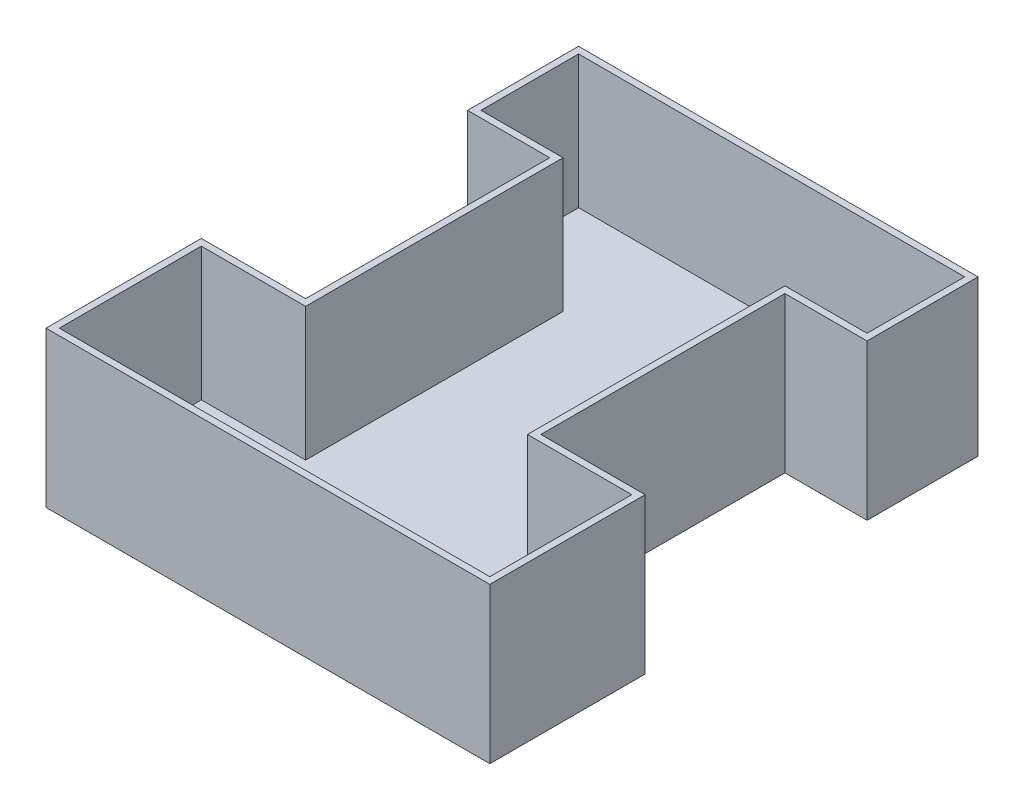
SolidWorks part; units mm, degrees
ref_plane "Front Plane" through (0, 0, 0) normal (0, 0, 1) x (1, 0, 0)
ref_plane "Top Plane" through (0, 0, 0) normal (0, 1, 0) x (1, 0, 0)
ref_plane "Right Plane" through (0, 0, 0) normal (1, 0, 0) x (0, 0, -1)
sketch "Sketch1" plane through (0, 0, 0) normal (0, 1, 0) x (1, 0, 0)
  line L0 (0, 77.0548) -> (0, -93.9041) construction
  line L1 (72.2603, 79.863) -> (-107.7397, 79.863)
  line L2 (-107.7397, 79.863) -> (-107.7397, 29.863)
  line L3 (-107.7397, 29.863) -> (-70.7397, 29.863)
  line L4 (-70.7397, 29.863) -> (-70.7397, -80.137)
  line L5 (-70.7397, -80.137) -> (-117.7397, -80.137)
  line L6 (-117.7397, -80.137) -> (-117.7397, -150.137)
  line L7 (-117.7397, -150.137) -> (82.2603, -150.137)
  line L8 (82.2603, -150.137) -> (82.2603, -80.137)
  line L9 (82.2603, -80.137) -> (35.2603, -80.137)
  line L10 (35.2603, -80.137) -> (35.2603, 29.863)
  line L11 (35.2603, 29.863) -> (72.2603, 29.863)
  line L12 (72.2603, 29.863) -> (72.2603, 79.863)
  line L13 (69.2603, 76.863) -> (-104.7397, 76.863)
  line L14 (-104.7397, 76.863) -> (-104.7397, 32.863)
  line L15 (-104.7397, 32.863) -> (-67.7397, 32.863)
  line L16 (-67.7397, 32.863) -> (-67.7397, -83.137)
  line L17 (-67.7397, -83.137) -> (-114.7397, -83.137)
  line L18 (-114.7397, -83.137) -> (-114.7397, -147.137)
  line L19 (-114.7397, -147.137) -> (79.2603, -147.137)
  line L20 (79.2603, -147.137) -> (79.2603, -83.137)
  line L21 (79.2603, -83.137) -> (32.2603, -83.137)
  line L22 (32.2603, -83.137) -> (32.2603, 32.863)
  line L23 (32.2603, 32.863) -> (69.2603, 32.863)
  line L24 (69.2603, 32.863) -> (69.2603, 76.863)
  dimension "D1" = 180
  dimension "D2" = 50
  dimension "D3" = 50
  dimension "D4" = 200
  dimension "D5" = 47
  dimension "D6" = 37
  dimension "D7" = 37
  dimension "D8" = 47
  dimension "D9" = 70
  dimension "D10" = 70
  dimension "D11" = 110
  dimension "D12" = 110
  dimension "D13" = 37
  dimension "D14" = 3
extrude "Boss-Extrude1" add sketch "Sketch1" along normal blind 60
sketch "Sketch2" plane through (0, 0, 0) normal (0, 1, 0) x (1, 0, 0)
  line L12 (72.2603, 29.863) -> (72.2603, 79.863)
  line L13 (72.2603, 79.863) -> (-107.7397, 79.863)
  line L14 (-107.7397, 79.863) -> (-107.7397, 29.863)
  line L15 (-107.7397, 29.863) -> (-70.7397, 29.863)
  line L16 (-70.7397, 29.863) -> (-70.7397, -80.137)
  line L17 (-70.7397, -80.137) -> (-117.7397, -80.137)
  line L18 (-117.7397, -80.137) -> (-117.7397, -150.137)
  line L19 (-117.7397, -150.137) -> (82.2603, -150.137)
  line L20 (82.2603, -150.137) -> (82.2603, -80.137)
  line L21 (82.2603, -80.137) -> (35.2603, -80.137)
  line L22 (35.2603, -80.137) -> (35.2603, 29.863)
  line L23 (35.2603, 29.863) -> (72.2603, 29.863)
  line L24 (72.2603, 29.863) -> (72.2603, 79.863)
  line L25 (72.2603, 79.863) -> (-107.7397, 79.863)
  line L26 (-107.7397, 79.863) -> (-107.7397, 29.863)
  line L27 (-107.7397, 29.863) -> (-70.7397, 29.863)
  line L28 (-70.7397, 29.863) -> (-70.7397, -80.137)
  line L29 (-70.7397, -80.137) -> (-117.7397, -80.137)
  line L30 (-117.7397, -80.137) -> (-117.7397, -150.137)
  line L31 (-117.7397, -150.137) -> (82.2603, -150.137)
  line L32 (82.2603, -150.137) -> (82.2603, -80.137)
  line L33 (82.2603, -80.137) -> (35.2603, -80.137)
  line L34 (35.2603, -80.137) -> (35.2603, 29.863)
  line L35 (35.2603, 29.863) -> (72.2603, 29.863)
  dimension "D1" = 0
extrude "Boss-Extrude2" add sketch "Sketch2" against normal blind 10
